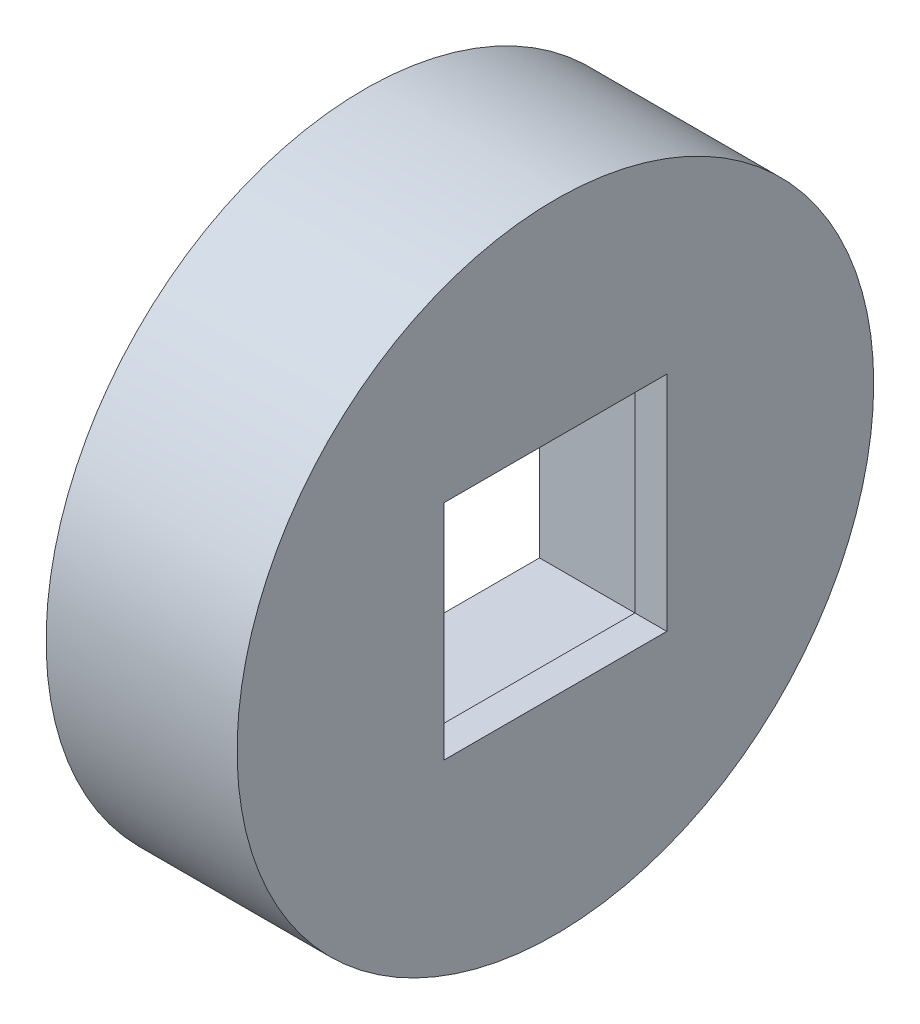
SolidWorks part; units mm, degrees
ref_plane "前视基准面" through (0, 0, 0) normal (0, 0, 1) x (1, 0, 0)
ref_plane "上视基准面" through (0, 0, 0) normal (0, 1, 0) x (1, 0, 0)
ref_plane "右视基准面" through (0, 0, 0) normal (1, 0, 0) x (0, 0, -1)
sketch "草图1" plane through (0, 0, 0) normal (1, 0, 0) x (0, 0, -1)
  line L1 (-2.75, -2.75) -> (2.75, -2.75)
  line L2 (-2.75, -2.75) -> (-2.75, 2.75)
  line L3 (-2.75, 2.75) -> (2.75, 2.75)
  line L4 (2.75, -2.75) -> (2.75, 2.75)
  line L5 (-2.75, -2.75) -> (2.75, 2.75) construction
  line L6 (-2.75, 2.75) -> (2.75, -2.75) construction
  circle A0 centre (0, 0) radius 5
  dimension "D3" = 10
  dimension "D1" = 5.5
  dimension "D2" = 5.5
extrude "凸台-拉伸1" add sketch "草图1" along normal blind 2.5
sketch "草图2" plane through (0, 0, 0) normal (-1, 0, 0) x (0, 0, 1)
  line L12 (-2.7, -2.7) -> (2.7, -2.7)
  line L13 (-2.7, 2.7) -> (-2.7, -2.7)
  line L14 (2.7, 2.7) -> (-2.7, 2.7)
  line L15 (2.7, -2.7) -> (2.7, 2.7)
  line L16 (-2.7, -2.7) -> (2.7, -2.7)
  line L17 (-2.7, 2.7) -> (-2.7, -2.7)
  line L18 (2.7, 2.7) -> (-2.7, 2.7)
  line L19 (2.7, -2.7) -> (2.7, 2.7)
  circle A1 centre (0, 0) radius 5
  circle A2 centre (0, 0) radius 5
  dimension "D1" = 0
  dimension "D2" = 0.05
sketch "草图3" plane through (2.5, 0, 0) normal (1, 0, 0) x (0, 0, -1)
  line L25 (1.75, 1.75) -> (-1.75, 1.75)
  line L26 (-1.75, 1.75) -> (-1.75, -1.75)
  line L27 (-1.75, -1.75) -> (1.75, -1.75)
  line L28 (1.75, -1.75) -> (1.75, 1.75)
  line L29 (1.75, 1.75) -> (-1.75, 1.75)
  line L30 (-1.75, 1.75) -> (-1.75, -1.75)
  line L31 (-1.75, -1.75) -> (1.75, -1.75)
  line L32 (1.75, -1.75) -> (1.75, 1.75)
  circle A0 centre (0, 0) radius 5 construction
  circle A1 centre (0, 0) radius 5
  circle M6 centre (0, 0) radius 5
  line M7 (-2.75, 2.75) -> (2.75, 2.75)
  line M8 (2.75, 2.75) -> (2.75, -2.75)
  line M9 (2.75, -2.75) -> (-2.75, -2.75)
  line M10 (-2.75, -2.75) -> (-2.75, 2.75)
  dimension "D1" = 1
extrude "凸台-拉伸3" add sketch "草图3" along normal blind 0.5 contours M6 M10 M7 M8 M9 | L32 L31 L30 L29 M7 M10 M9 M8 | A1
